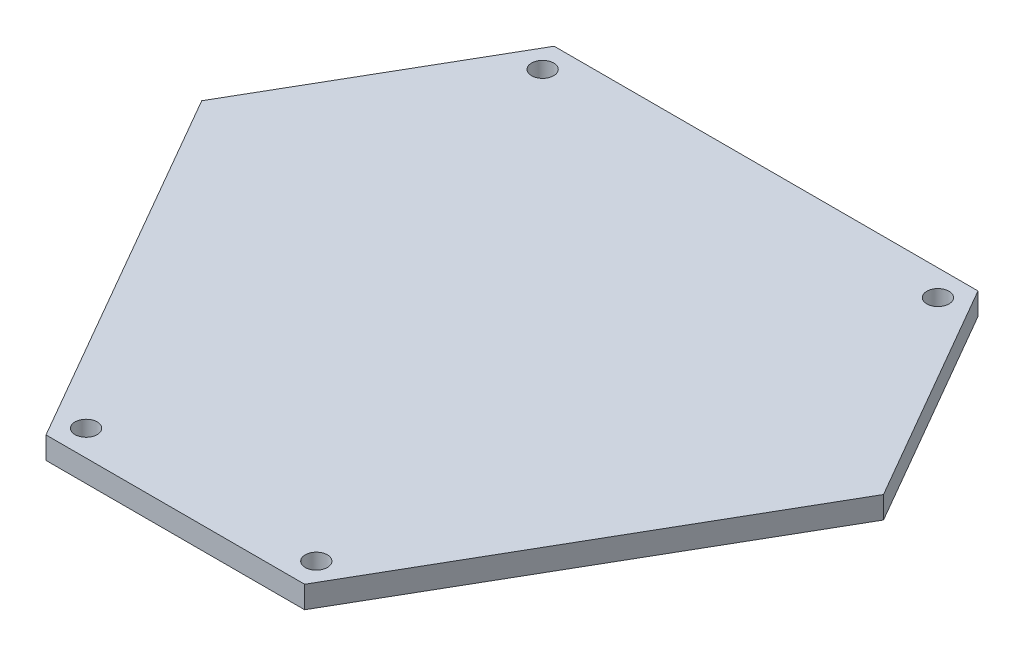
SolidWorks part; units mm, degrees
ref_plane "Plano frontal" through (0, 0, 0) normal (0, 0, 1) x (1, 0, 0)
ref_plane "Plano superior" through (0, 0, 0) normal (0, 1, 0) x (1, 0, 0)
ref_plane "Plano direito" through (0, 0, 0) normal (1, 0, 0) x (0, 0, -1)
sketch "Esboço1" plane through (0, 0, 0) normal (0, 1, 0) x (1, 0, 0)
  line L4 (0, 0) -> (0, 129.9) construction
  line L5 (-75, 0) -> (75, 0)
  line L8 (0, 129.9) -> (-75, 0)
  line L9 (0, 129.9) -> (75, 0)
  point P5 (0, 0)
  dimension "D1" = 129.9
  dimension "D2" = 150
extrude "Ressalto-extrusão1" add sketch "Esboço1" along normal blind 3
sketch "Esboço4" plane through (0, 3, 0) normal (0, 1, 0) x (1, 0, 0)
  line L0 (-28.7426, 80.1178) -> (28.7426, 80.1178)
  line L1 (0, 129.9) -> (-75, 0) construction
  line L2 (75, 0) -> (0, 129.9) construction
  line L5 (-75, 0) -> (75, 0) construction
  line L7 (-46.2393, 49.8136) -> (-17.5486, 0)
  line L10 (-46.2393, 49.8136) -> (-75, 0)
  line L11 (28.7426, 80.1178) -> (0, 129.9)
  line L12 (17.5322, 0) -> (75, 0)
  line L13 (46.2474, 49.7995) -> (17.5322, 0)
  line L16 (-75, 0) -> (75, 0)
  line L18 (75, 0) -> (0, 129.9)
  line L20 (0, 129.9) -> (-75, 0)
  line L22 (-75, 0) -> (-17.5486, 0)
  line L24 (75, 0) -> (46.2474, 49.7995)
  line L26 (0, 129.9) -> (-28.7426, 80.1178)
  dimension "D1" = 49.7843
  dimension "D2" = 0
  dimension "D3" = 49.7822
  dimension "D4" = 49.7844
  dimension "D5" = 60.032
  dimension "D6" = 60.06
extrude "Corte-extrusão2" cut sketch "Esboço4" against normal through all
sketch "Esboço5" plane through (0, 3, 0) normal (0, 1, 0) x (1, 0, 0)
  line L0 (0, 0) -> (0, 80.1178) construction
  line L1 (-28.7426, 80.1178) -> (28.7426, 80.1178) construction
  line L2 (-17.5486, 0) -> (17.5322, 0) construction
  circle A0 centre (-26.8061, 76.6178) radius 1.5
  circle A1 centre (26.8061, 76.6178) radius 1.5
  circle A2 centre (-15.6121, 3.5) radius 1.5
  circle A3 centre (15.6121, 3.5) radius 1.5
  dimension "D1" = 3
  dimension "D2" = 4
  dimension "D3" = 4
  dimension "D4" = 3.5
  dimension "D5" = 3.5
extrude "Corte-extrusão3" cut sketch "Esboço5" against normal through all
